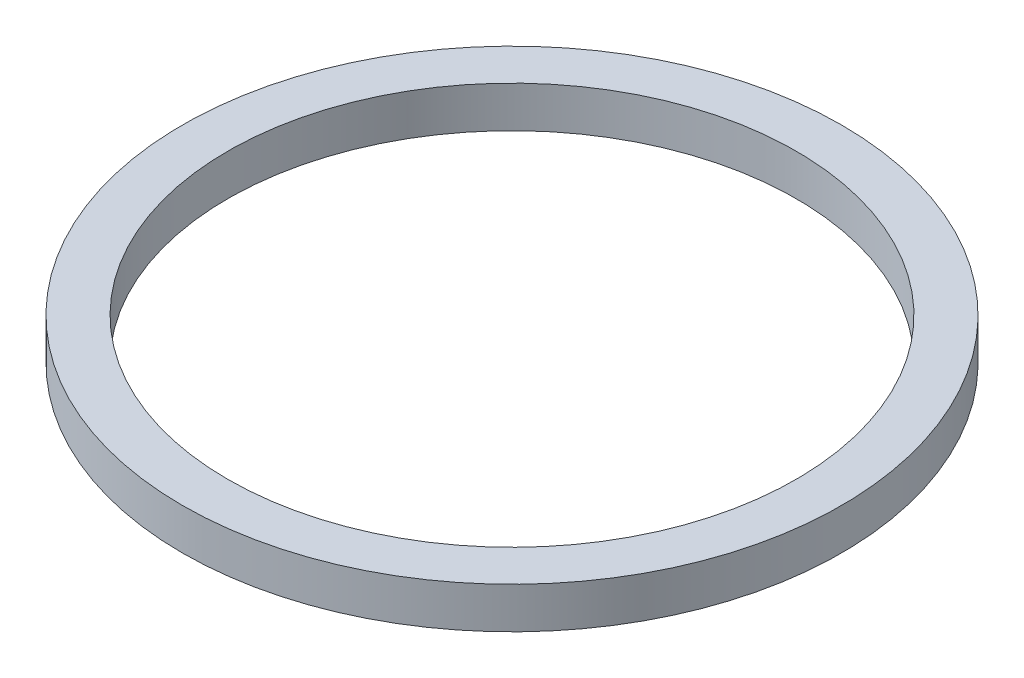
SolidWorks part; units mm, degrees
ref_plane "Front Plane" through (0, 0, 0) normal (0, 0, 1) x (1, 0, 0)
ref_plane "Top Plane" through (0, 0, 0) normal (0, 1, 0) x (1, 0, 0)
ref_plane "Right Plane" through (0, 0, 0) normal (1, 0, 0) x (0, 0, -1)
sketch "Sketch1" plane through (0, 0, 0) normal (0, 1, 0) x (1, 0, 0)
  circle A0 centre (0, 0) radius 69
  circle A1 centre (0, 0) radius 80
extrude "Boss-Extrude1" add sketch "Sketch1" along normal blind 10
